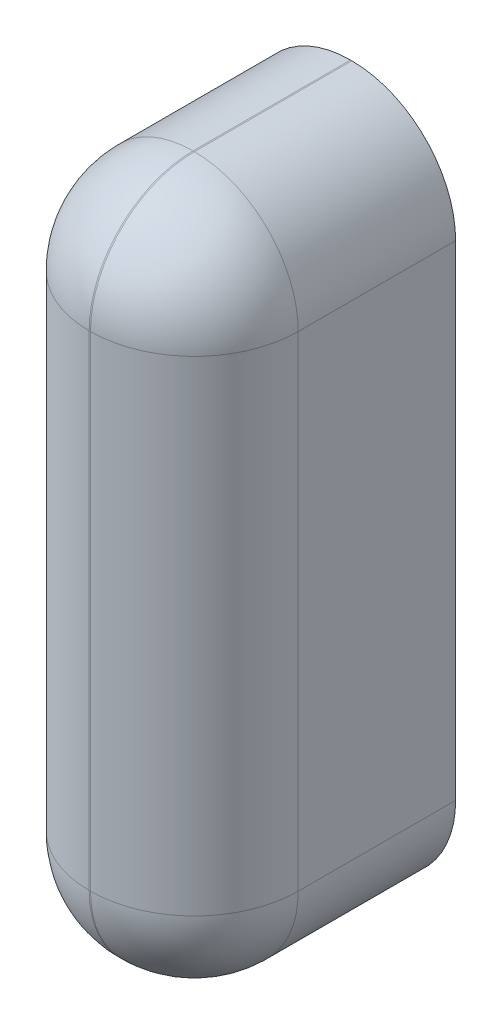
SolidWorks part; units mm, degrees
ref_plane "Спереди" through (0, 0, 0) normal (0, 0, 1) x (1, 0, 0)
ref_plane "Сверху" through (0, 0, 0) normal (0, 1, 0) x (1, 0, 0)
ref_plane "Справа" through (0, 0, 0) normal (1, 0, 0) x (0, 0, -1)
sketch "Эскиз1" plane through (0, 0, 0) normal (0, 0, 1) x (1, 0, 0)
  line L1 (-0.01, -5.3) -> (0.01, -5.3)
  line L2 (-1.6, -3.71) -> (-1.6, 3.71)
  line L3 (-0.01, 5.3) -> (0.01, 5.3)
  line L4 (1.6, -3.71) -> (1.6, 3.71)
  line L5 (-1.6, -5.3) -> (1.6, 5.3) construction
  line L6 (-1.6, 5.3) -> (1.6, -5.3) construction
  arc A0 (0.01, -5.3) -> (1.6, -3.71) centre (0.01, -3.71) ccw
  arc A1 (-0.01, -5.3) -> (-1.6, -3.71) centre (-0.01, -3.71) cw
  arc A2 (0.01, 5.3) -> (1.6, 3.71) centre (0.01, 3.71) cw
  arc A3 (-0.01, 5.3) -> (-1.6, 3.71) centre (-0.01, 3.71) ccw
  point P0 (0, 0)
  dimension "D3" = 1.59
  dimension "D1" = 3.2
  dimension "D2" = 10.6
extrude "Бобышка-Вытянуть1" add sketch "Эскиз1" along normal blind 4
fillet "Скругление1" radius 1.59 8 edges at (0, 5.3, 4) (0, -5.3, 4) (1.1343, -4.8343, 4) (-1.1343, -4.8343, 4) (1.6, 0, 4) (1.1343, 4.8343, 4) (-1.1343, 4.8343, 4) (-1.6, 0, 4)
